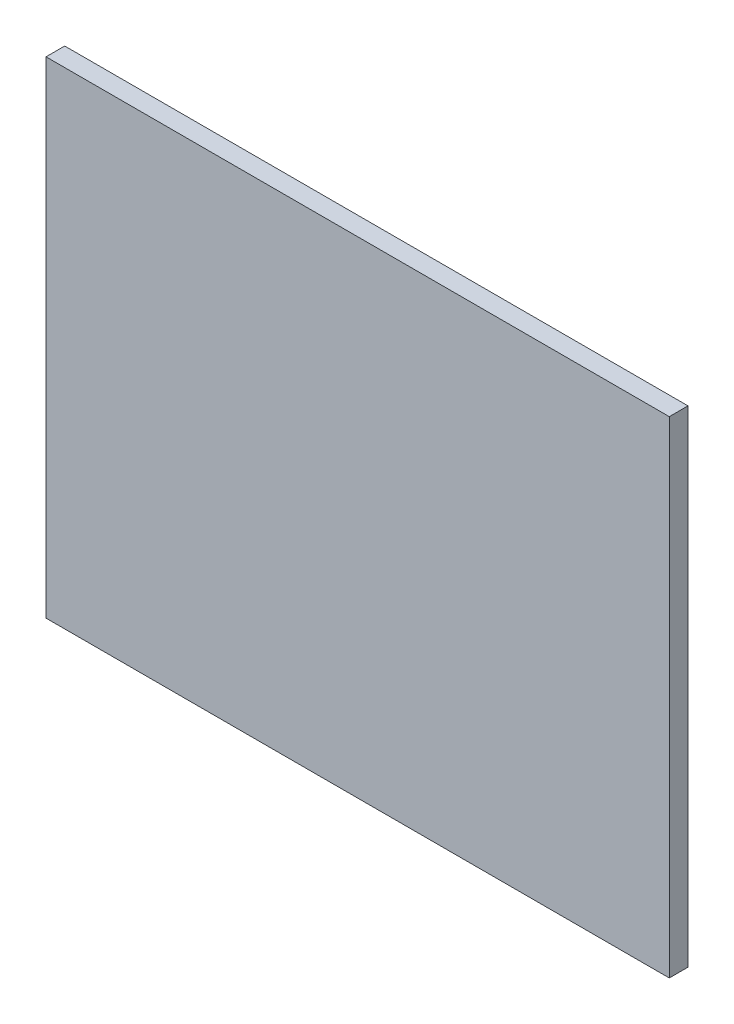
SolidWorks part; units mm, degrees
ref_plane "Plano frontal" through (0, 0, 0) normal (0, 0, 1) x (1, 0, 0)
ref_plane "Plano superior" through (0, 0, 0) normal (0, 1, 0) x (1, 0, 0)
ref_plane "Plano direito" through (0, 0, 0) normal (1, 0, 0) x (0, 0, -1)
sketch "Esboço1" plane through (0, 0, 0) normal (0, 0, 1) x (1, 0, 0)
  line L1 (-250, 195) -> (250, 195)
  line L2 (-250, 195) -> (-250, -195)
  line L3 (-250, -195) -> (250, -195)
  line L4 (250, 195) -> (250, -195)
  line L5 (-250, 195) -> (250, -195) construction
  line L6 (-250, -195) -> (250, 195) construction
  point P0 (0, 0)
  dimension "D1" = 390
  dimension "D2" = 500
extrude "Ressalto-extrusão1" add sketch "Esboço1" along normal blind 15
